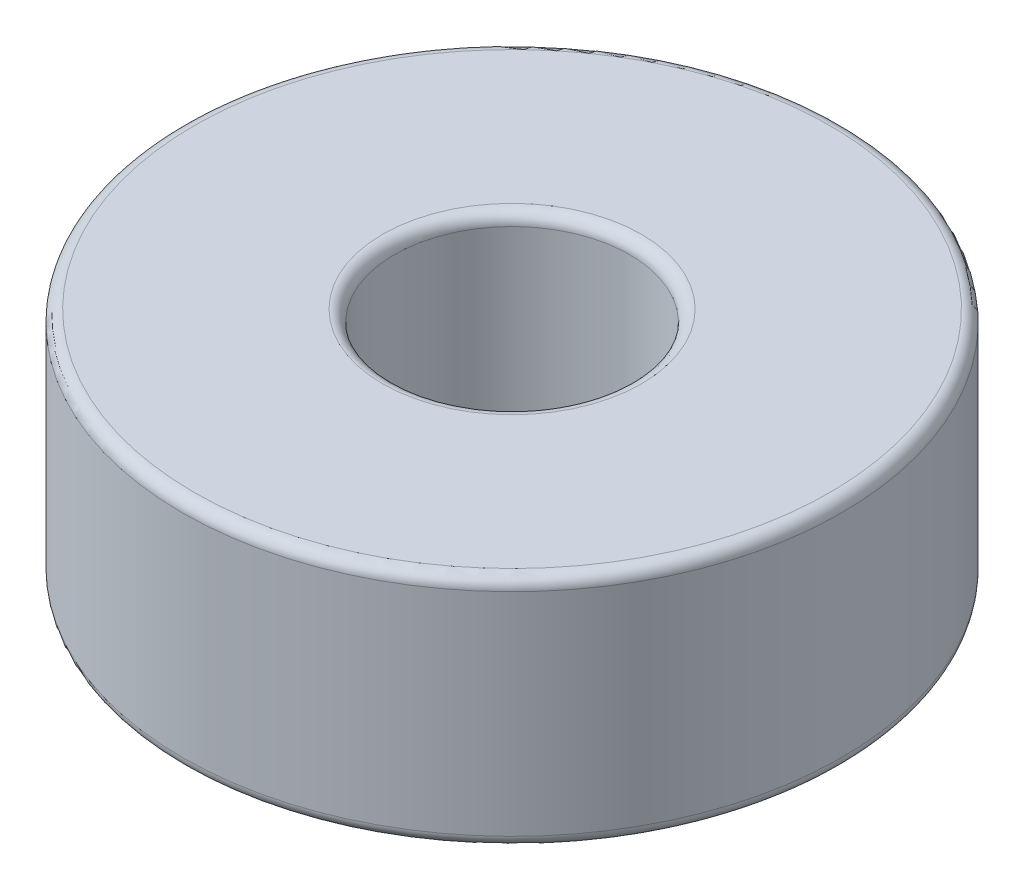
SolidWorks part; units mm, degrees
ref_plane "Front Plane" through (0, 0, 0) normal (0, 0, 1) x (1, 0, 0)
ref_plane "Top Plane" through (0, 0, 0) normal (0, 1, 0) x (1, 0, 0)
ref_plane "Right Plane" through (0, 0, 0) normal (1, 0, 0) x (0, 0, -1)
sketch "Sketch1" plane through (0, 0, 0) normal (0, 1, 0) x (1, 0, 0)
  circle A0 centre (0, 0) radius 2.5
  circle A1 centre (0, 0) radius 7
  dimension "D1" = 5
  dimension "D2" = 14
extrude "Boss-Extrude1" add sketch "Sketch1" along normal blind 5
fillet "Fillet1" radius 0.25 4 edges at (0, 0, 7) (0, 5, 7) (0, 0, 2.5) (0, 5, 2.5)
